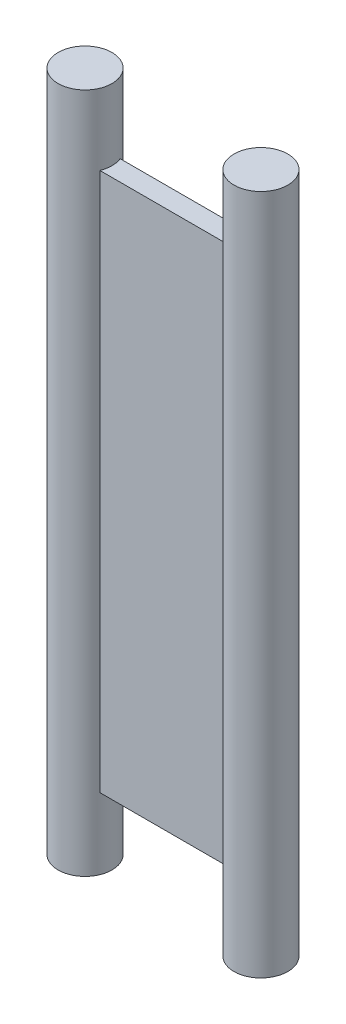
SolidWorks part; units mm, degrees
ref_plane "Front Plane" through (0, 0, 0) normal (0, 0, 1) x (1, 0, 0)
ref_plane "Top Plane" through (0, 0, 0) normal (0, 1, 0) x (1, 0, 0)
ref_plane "Right Plane" through (0, 0, 0) normal (1, 0, 0) x (0, 0, -1)
sketch "Sketch1" plane through (0, 0, 0) normal (0, 1, 0) x (1, 0, 0)
  line L1 (4.325, 0.5) -> (-4.325, 0.5)
  line L2 (4.325, 0.5) -> (4.325, -0.5)
  line L3 (4.325, -0.5) -> (-4.325, -0.5)
  line L4 (-4.325, 0.5) -> (-4.325, -0.5)
  line L5 (4.325, 0.5) -> (-4.325, -0.5) construction
  line L6 (4.325, -0.5) -> (-4.325, 0.5) construction
  point P0 (0, 0)
  dimension "D1" = 8.65
  dimension "D3" = 1
extrude "Boss-Extrude1" add sketch "Sketch1" along normal blind 26.5
ref_plane "Plane1" through (0, 13.25, 0) normal (0, 1, 0) x (1, 0, 0)
sketch "Sketch2" plane through (0, 13.25, 0) normal (0, 1, 0) x (1, 0, 0)
  line L0 (4.325, -0.5) -> (4.325, 0.5) construction
  line L1 (-4.325, 0.5) -> (-4.325, -0.5) construction
  line L2 (4.325, -0.5) -> (4.325, 0.5) construction
  line L3 (-4.325, 0.5) -> (-4.325, -0.5) construction
  circle A0 centre (-4.325, 0) radius 1.325
  circle A1 centre (4.325, 0) radius 1.325
  dimension "D1" = 2.65
extrude "Boss-Extrude2" add sketch "Sketch2" along normal mid plane 33.5
